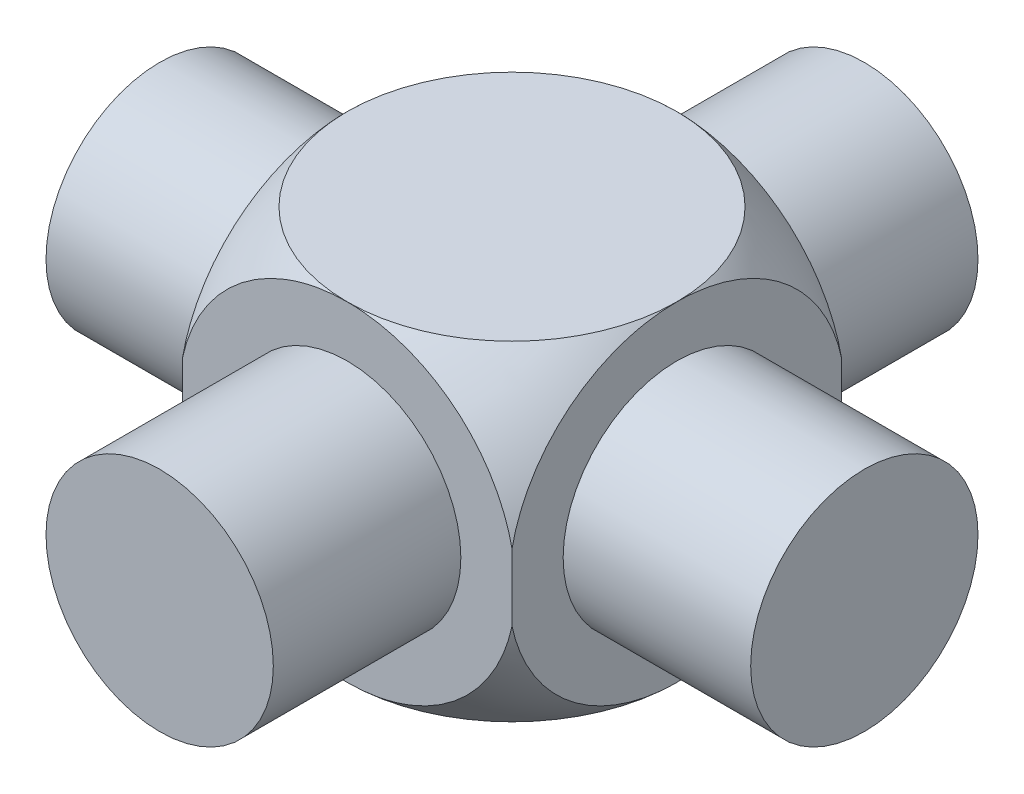
SolidWorks part; units mm, degrees
ref_plane "Front Plane" through (0, 0, 0) normal (0, 0, 1) x (1, 0, 0)
ref_plane "Top Plane" through (0, 0, 0) normal (0, 1, 0) x (1, 0, 0)
ref_plane "Right Plane" through (0, 0, 0) normal (1, 0, 0) x (0, 0, -1)
sketch "Sketch1" plane through (0, 0, 0) normal (0, 0, 1) x (1, 0, 0)
  line L1 (-7.25, -7.25) -> (7.25, -7.25)
  line L2 (-7.25, -7.25) -> (-7.25, 7.25)
  line L3 (-7.25, 7.25) -> (7.25, 7.25)
  line L4 (7.25, -7.25) -> (7.25, 7.25)
  line L5 (-7.25, -7.25) -> (7.25, 7.25) construction
  line L6 (-7.25, 7.25) -> (7.25, -7.25) construction
  point P0 (0, 0)
  dimension "D1" = 14.5
  dimension "D2" = 14.5
extrude "Boss-Extrude1" add sketch "Sketch1" along normal blind 14.5
sketch "Sketch2" plane through (0, 7.25, 0) normal (0, 1, 0) x (1, 0, 0)
  line L0 (7.25, -14.5) -> (-7.25, -14.5) construction
  circle A0 centre (0, -7.25) radius 7.25
  dimension "D1" = 14.5
ref_plane "Plane1" through (3.625, 0, 3.625) normal (-0.7071, 0, -0.7071) x (-0.7071, 0, 0.7071)
sketch "Sketch5" plane through (3.625, 0, 3.625) normal (-0.7071, 0, -0.7071) x (-0.7071, 0, 0.7071)
  line L0 (5.1265, 7.25) -> (5.1265, -3.292) construction
  line L1 (12.3765, 7.25) -> (16.8468, 7.25)
  line L2 (16.8468, 7.25) -> (16.8468, -7.25)
  line L3 (15.3796, -7.25) -> (5.1265, -7.25) construction
  line L4 (16.8468, -7.25) -> (12.3765, -7.25)
  line L5 (12.3765, 7.25) -> (-2.1235, 7.25) construction
  line L6 (5.1265, -7.25) -> (5.1265, 7.25) construction
  arc A0 (12.3765, 7.25) -> (12.3765, -7.25) centre (5.489, 0) cw
  dimension "D1" = 10
revolve "Cut-Revolve1" cut sketch "Sketch5" angle 360 about L0
sketch "Sketch6" plane through (0, 0, 0) normal (1, 0, 0) x (0, 0, -1)
  circle A0 centre (-7.25, 0) radius 5
  dimension "D2" = 10
  dimension "D1" = 7.25
extrude "Boss-Extrude2" add sketch "Sketch6" along normal mid plane 31
ref_plane "Plane2" through (0, 0, 7.25) normal (0, 0, -1) x (-1, 0, 0)
sketch "Sketch7" plane through (0, 0, 7.25) normal (0, 0, -1) x (-1, 0, 0)
  circle A0 centre (0, 0) radius 5
  dimension "D1" = 10
extrude "Boss-Extrude3" add sketch "Sketch7" along normal mid plane 31
